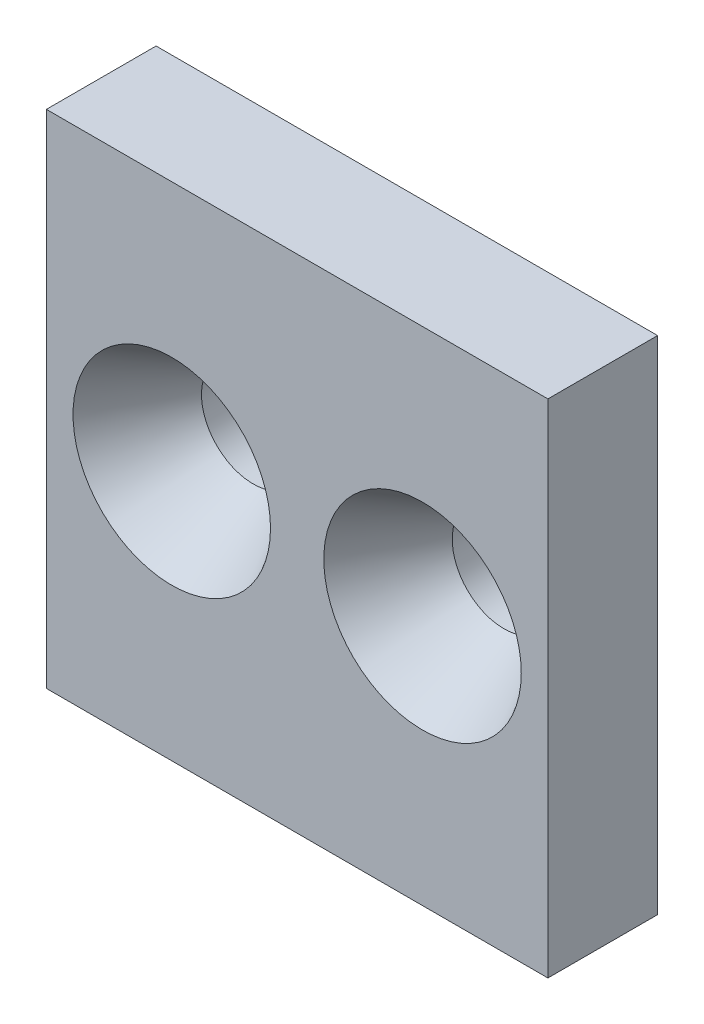
SolidWorks part; units mm, degrees
ref_plane "Front Plane" through (0, 0, 0) normal (0, 0, 1) x (1, 0, 0)
ref_plane "Top Plane" through (0, 0, 0) normal (0, 1, 0) x (1, 0, 0)
ref_plane "Right Plane" through (0, 0, 0) normal (1, 0, 0) x (0, 0, -1)
sketch "Sketch1" plane through (0, 0, 0) normal (0, 0, 1) x (1, 0, 0)
  line L0 (0, 0) -> (0, 16) construction
  line L1 (0, 0) -> (32, 0)
  line L2 (0, 0) -> (0, 32)
  line L3 (0, 32) -> (32, 32)
  line L4 (32, 0) -> (32, 32)
  line L5 (0, 16) -> (32, 16) construction
extrude "Extrude2" add sketch "Sketch1" along normal blind 7
hole_wizard "CSK for M6 Flat Head Machine Screw1" positions "3DSketch1" profile "Sketch2" countersink size "M6" standard "Ansi Metric" end condition through all
sketch3d "3DSketch1"
  line L0 (0, 0, 7) -> (32, 0, 7) construction
  line L1 (0, 32, 7) -> (0, 0, 7) construction
  point P0 (8, 16, 7)
  point P2 (24, 16, 7)
  dimension "D1" = 16
  dimension "D2" = 16
  dimension "D3" = 8
  dimension "D4" = 16
sketch "Sketch2" plane through (8, 16, 7) normal (1, 0, 0) x (0, -1, 0)
  line L0 (0, 0) -> (0, 7)
  line L1 (0, 7) -> (3.3, 7)
  line L2 (3.3, 7) -> (3.3, 5.1962)
  line L3 (3.3, 5.1962) -> (6.3, 0)
  line L5 (6.3, 0) -> (0, 0)
  line L6 (-3.3, 5.1962) -> (-6.3, 0) construction
  line L11 (0, -6.35) -> (0, 107.95) construction
  dimension "Thru Hole Dia." = 6.6
  dimension "Thru Hole Depth" = 7
  dimension "Near C'Sink Dia." = 12.6
  dimension "Near C'Sink Angle" = 60
